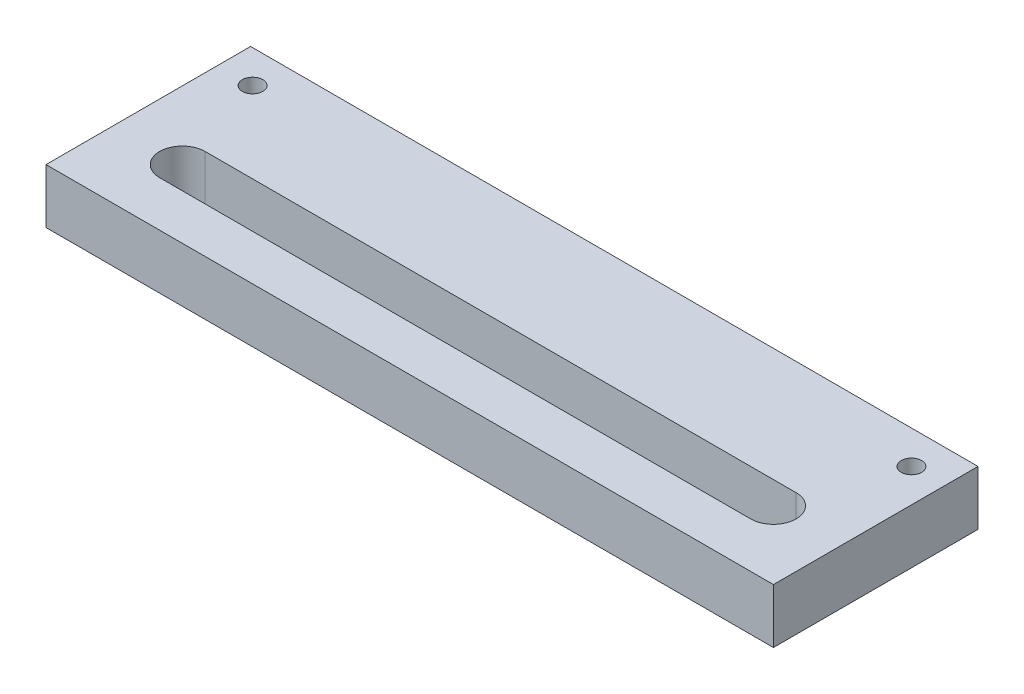
SolidWorks part; units mm, degrees
ref_plane "Front Plane" through (0, 0, 0) normal (0, 0, 1) x (1, 0, 0)
ref_plane "Top Plane" through (0, 0, 0) normal (0, 1, 0) x (1, 0, 0)
ref_plane "Right Plane" through (0, 0, 0) normal (1, 0, 0) x (0, 0, -1)
sketch "Sketch1" plane through (0, 0, 0) normal (0, 1, 0) x (1, 0, 0)
  line L1 (0, 0) -> (-160, 0)
  line L2 (0, 0) -> (0, -45)
  line L3 (0, -45) -> (-160, -45)
  line L4 (-160, 0) -> (-160, -45)
  dimension "D1" = 160
  dimension "D2" = 45
extrude "Boss-Extrude1" add sketch "Sketch1" along normal blind 12
sketch "Sketch2" plane through (0, 12, 0) normal (0, 1, 0) x (1, 0, 0)
hole_wizard "CBORE for M5 Hex Head Bolt5" positions "Sketch11" profile "Sketch12" counterbore size "M5" standard "ISO" end condition through all
sketch "Sketch11" plane through (0, 0, 0) normal (0, -1, 0) x (-1, 0, 0)
  point P0 (152.3349, -7.2223)
sketch "Sketch12" plane through (-152.3349, 0, 7.2223) normal (1, 0, 0) x (0, 0, -1)
  line L0 (0, 0) -> (0, 12)
  line L1 (0, 12) -> (2.25, 12)
  line L3 (2.25, 12) -> (2.25, 5)
  line L4 (2.25, 5) -> (5, 5)
  line L5 (5, 5) -> (5, 0)
  line L7 (5, 0) -> (0, 0)
  line L11 (0, -6.35) -> (0, 107.95) construction
  dimension "Thru Hole Dia." = 4.5
  dimension "Thru Hole Depth" = 12
  dimension "C'Bore Dia." = 10
  dimension "C'Bore Depth" = 5
hole_wizard "CBORE for M5 Hex Head Bolt7" positions "Sketch15" profile "Sketch16" counterbore size "M5" standard "ISO" end condition through all
sketch "Sketch15" plane through (0, 0, 0) normal (0, -1, 0) x (-1, 0, 0)
  point P0 (7.32, -7.32)
  point P2 (7.32, -7.32)
sketch "Sketch16" plane through (-7.32, 0, 7.32) normal (1, 0, 0) x (0, 0, -1)
  line L0 (0, 0) -> (0, 12)
  line L1 (0, 12) -> (2.25, 12)
  line L3 (2.25, 12) -> (2.25, 5)
  line L4 (2.25, 5) -> (5, 5)
  line L5 (5, 5) -> (5, 0)
  line L7 (5, 0) -> (0, 0)
  line L11 (0, -6.35) -> (0, 107.95) construction
  dimension "Thru Hole Dia." = 4.5
  dimension "Thru Hole Depth" = 12
  dimension "C'Bore Dia." = 10
  dimension "C'Bore Depth" = 5
sketch "Sketch17" plane through (0, 0, 0) normal (0, -1, 0) x (-1, 0, 0)
  line L0 (160, -45) -> (160, -30)
  line L1 (160, 0) -> (160, -45) construction
  line L2 (160, -45) -> (145, -45)
  line L3 (160, -45) -> (0, -45) construction
  line L4 (0, -45) -> (15, -45)
  line L5 (0, -45) -> (0, -30)
  line L6 (0, -45) -> (0, 0) construction
  line L8 (145, -45) -> (145, -30)
  line L9 (145, -30) -> (145, -45)
  line L10 (15, -45) -> (15, -30)
  line L11 (145, -35) -> (99.0029, -35)
  line L12 (99.0029, -35) -> (15, -35)
  line L13 (145, -25) -> (15, -25)
  circle A0 centre (145, -30) radius 5
  circle A1 centre (15, -30) radius 5
  dimension "D5" = 10
  dimension "D6" = 10
  dimension "D1" = 15
  dimension "D2" = 15
  dimension "D3" = 15
  dimension "D4" = 15
extrude "Cut-Extrude4" cut sketch "Sketch17" against normal blind 12
